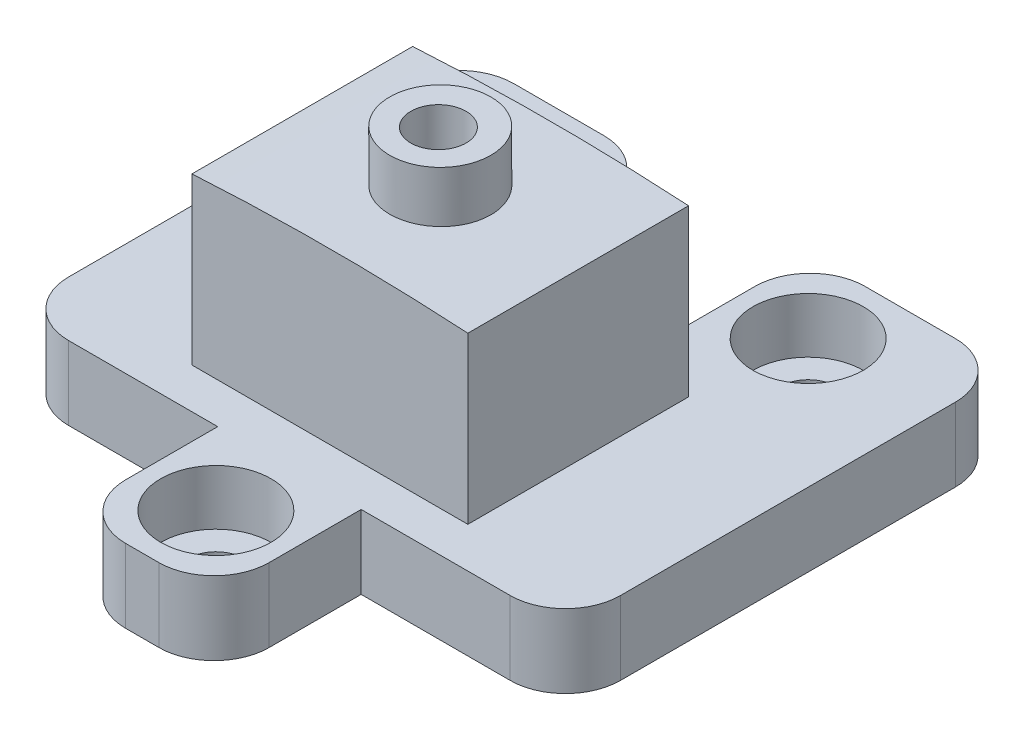
SolidWorks part; units mm, degrees
ref_plane "Front Plane" through (0, 0, 0) normal (0, 0, 1) x (1, 0, 0)
ref_plane "Top Plane" through (0, 0, 0) normal (0, 1, 0) x (1, 0, 0)
ref_plane "Right Plane" through (0, 0, 0) normal (1, 0, 0) x (0, 0, -1)
sketch "草图2" plane through (0, 0, 0) normal (0, 1, 0) x (1, 0, 0)
  line L0 (0, -1000) -> (0, 49000) construction
  line L1 (-8, -12.1) -> (8, -12.1) construction
  line L2 (-8, -12.1) -> (-8, 12.1) construction
  line L3 (-8, 12.1) -> (8, 12.1) construction
  line L4 (8, -12.1) -> (8, 12.1) construction
  line L5 (-8, -12.1) -> (8, 12.1) construction
  line L6 (-8, 12.1) -> (8, -12.1) construction
  line L7 (-19.5, -1001.2889) -> (-19.5, 48998.7111) construction
  line L8 (19.5, -1000.9497) -> (19.5, 48999.0503) construction
  circle A2 centre (-8, 12.1) radius 1.5
  circle A3 centre (8, 12.1) radius 1.5
  circle A4 centre (0, -12.1) radius 1.5
  point P0 (0, 0)
  dimension "D3" = 3
  dimension "D4" = 3
  dimension "D5" = 3
  dimension "D1" = 24.2
  dimension "D2" = 16
  dimension "D6" = 39
  dimension "D7" = 19.5
sketch "草图1" plane through (0, 0, 0) normal (0, 1, 0) x (1, 0, 0)
  line L0 (-15, 16.1) -> (-4.1, 16.1)
  line L1 (-4.1, 16.1) -> (-4.1, 8.1)
  line L2 (-4.1, 8.1) -> (4.1, 8.1)
  line L3 (4.1, 8.1) -> (4.1, 16.1)
  line L4 (4.1, 16.1) -> (15, 16.1)
  line L5 (15, 16.1) -> (15, -8.1)
  line L6 (15, -8.1) -> (3.9, -8.1)
  line L7 (3.9, -8.1) -> (3.9, -16.1)
  line L8 (3.9, -16.1) -> (-3.9, -16.1)
  line L9 (-3.9, -16.1) -> (-3.9, -8.1)
  line L10 (-3.9, -8.1) -> (-15, -8.1)
  line L11 (-15, -8.1) -> (-15, 16.1)
  line L12 (0, -2027.683) -> (0, 99356.4666) construction
  line L13 (-8, -12.1) -> (8, -12.1) construction
  line L14 (-8, 12.1) -> (8, 12.1) construction
  point P34 (-3.9, -12.1)
  point P37 (-4.1, 12.1)
  dimension "D1" = 30
  dimension "D2" = 7.8
  dimension "D3" = 8.2
  dimension "D4" = 8
  dimension "D5" = 8
extrude "凸台-拉伸1" add sketch "草图1" along normal blind 4
extrude "切除-拉伸2" cut sketch "草图2" along normal through all
sketch "草图3" plane through (0, 4, 0) normal (0, 1, 0) x (1, 0, 0)
  line L0 (-8, -12.1) -> (8, -12.1) construction
  circle A0 centre (-8, 12.1) radius 3
  circle A1 centre (8, 12.1) radius 3
  circle A2 centre (0, -12.1) radius 3
  dimension "D1" = 6
  dimension "D2" = 6
  dimension "D3" = 6
extrude "切除-拉伸3" cut sketch "草图3" against normal blind 3
fillet "圆角1" radius 3 8 edges at (3.9, 2, 16.1) (-3.9, 2, 16.1) (-15, 2, 8.1) (15, 2, 8.1) (15, 2, -16.1) (-15, 2, -16.1) (4.1, 2, -16.1) (-4.1, 2, -16.1)
sketch "草图4" plane through (0, 4, 0) normal (0, 1, 0) x (1, 0, 0)
  line L0 (4.1, 8.1) -> (-4.1, 8.1) construction
  line L1 (-7.5, 6.1) -> (7.5, 6.1)
  line L2 (-7.5, 6.1) -> (-7.5, -5.9)
  line L3 (-7.5, -5.9) -> (7.5, -5.9)
  line L4 (7.5, 6.1) -> (7.5, -5.9)
  point P8 (0, 6.1)
  dimension "D1" = 2
  dimension "D2" = 12
  dimension "D3" = 15
  dimension "D4" = 12
extrude "凸台-拉伸2" add sketch "草图4" along normal blind 10
sketch "草图8" plane through (0, 0, -6.1) normal (0, 0, -1) x (-1, 0, 0)
  line L0 (-7.5, 14) -> (-7.5, 4) construction
  line L1 (7.5, 14) -> (7.5, 4) construction
  line L2 (0, 13.2252) -> (0, -111.7748) construction
  line L3 (-7.5, 13) -> (-7.5, 14)
  line L4 (-7.5, 14) -> (7.5, 14)
  line L5 (7.5, 14) -> (7.5, 13)
  arc A0 (-7.5, 13) -> (7.5, 13) centre (0, -111.7748) cw
  dimension "D1" = 125
  dimension "D2" = 1
extrude "切除-拉伸7" cut sketch "草图8" against normal through all
ref_plane "基准面1" through (0, 13, 0) normal (0, -1, 0) x (-1, 0, 0)
sketch "草图9" plane through (0, 13, 0) normal (0, -1, 0) x (-1, 0, 0)
  line L0 (7.5, 6.1) -> (-7.5, -5.9) construction
  circle A0 centre (0, 0.1) radius 2.75
  dimension "D1" = 5.5
extrude "凸台-拉伸3" add sketch "草图9" against normal blind 3
sketch "草图10" plane through (0, 16, 0) normal (0, 1, 0) x (1, 0, 0)
  circle A0 centre (0, 0) radius 1.5
  dimension "D1" = 3
extrude "切除-拉伸8" cut sketch "草图10" against normal through all
sketch "草图11" plane through (0, 0, 0) normal (0, -1, 0) x (1, 0, 0)
  line L1 (3.1754, 0) -> (1.5877, 2.75)
  line L2 (1.5877, 2.75) -> (-1.5877, 2.75)
  line L3 (-1.5877, 2.75) -> (-3.1754, 0)
  line L4 (-3.1754, 0) -> (-1.5877, -2.75)
  line L5 (-1.5877, -2.75) -> (1.5877, -2.75)
  line L6 (1.5877, -2.75) -> (3.1754, 0)
  circle A0 centre (0, 0) radius 2.75 construction
  dimension "D1" = 5.5
extrude "切除-拉伸9" cut sketch "草图11" against normal offset from surface (10.2149 mm away) 3
sketch "草图12" plane through (0, 0, 0) normal (0, -1, 0) x (1, 0, 0)
  line L1 (-4, -3) -> (4, -3)
  line L2 (-4, -3) -> (-4, 3)
  line L3 (-4, 3) -> (4, 3)
  line L4 (4, -3) -> (4, 3)
  line L5 (-4, -3) -> (4, 3) construction
  line L6 (-4, 3) -> (4, -3) construction
  point P0 (0, 0)
  dimension "D1" = 8
  dimension "D2" = 6
extrude "切除-拉伸13" cut sketch "草图12" against normal offset from surface (7.158 mm away) 6
